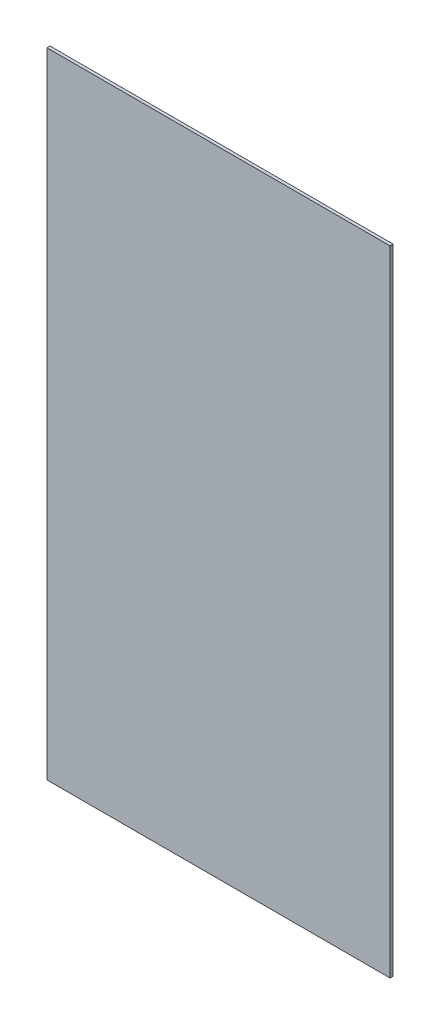
SolidWorks part; units mm, degrees
ref_plane "Front Plane" through (0, 0, 0) normal (0, 0, 1) x (1, 0, 0)
ref_plane "Top Plane" through (0, 0, 0) normal (0, 1, 0) x (1, 0, 0)
ref_plane "Right Plane" through (0, 0, 0) normal (1, 0, 0) x (0, 0, -1)
ref_plane "PZ 26.850" through (0, 0, 26.85) normal (0, 0, 1) x (1, 0, 0)
sketch "diffuser sketch" plane through (0, 0, 26.85) normal (0, 0, 1) x (1, 0, 0)
  line L0 (-164.7, -304.4) -> (164.7, -304.4)
  line L1 (164.7, -304.4) -> (164.7, 304.4)
  line L2 (164.7, 304.4) -> (-164.7, 304.4)
  line L3 (-164.7, 304.4) -> (-164.7, -304.4)
extrude "diffuser" add sketch "diffuser sketch" along normal mid plane 2.9
equation "\"diffL\" = 608.8mm"
equation "\"diffW\" = 329.4mm"
equation "\"diffT\" = 2.9mm"
equation "\"chanSlotW\" = 12.9mm"
equation "\"chanSlotDepth\" = 11.13mm"
equation "\"chanFloor\" = 1.57mm"
equation "\"chanLeg\" = 12.7mm"
equation "\"lightL\" = 604.8mm"
equation "\"lightW\" = 330.2mm"
equation "\"lightH\" = 92mm"
equation "\"lightSideFlat\" = 30mm"
equation "\"lightSlopeLen\" = 38.9mm"
equation "\"lightWingDepth\" = 50.1mm"
equation "\"lightWingFlat\" = 90.2mm"
equation "\"lightChanW\" = 99.6mm"
equation "\"lightChanStand\" = 44.1mm"
equation "\"insFlangeD\" = 12.3mm"
equation "\"insFromEnd\" = 20.7mm"
equation "\"insUpSlope\" = 20.8mm"
equation "\"gaugeH\" = 10mm"
equation "\"gaugeStepLen\" = 14mm"
equation "\"gaugeStepW0\" = 13.1mm"
equation "\"gaugeStepDW\" = 0.2mm"
equation "\"gaugeSteps\" = 5mm"
equation "\"gaugeHandleLen\" = 30mm"
equation "\"gaugeHandleW\" = 24mm"
equation "\"gaugeSlot0\" = 3mm"
equation "\"gaugeSlotD\" = 0.1mm"
equation "\"gaugeSlotDepth\" = 8mm"
equation "\"gap\" = 25.4mm"
equation "\"edgeL\" = 1mm"
equation "\"edgeW\" = 0.75mm"
equation "\"proud\" = 2.5mm"
equation "\"seatClr\" = 0.15mm"
equation "\"tongueClrZ\" = 0.1mm"
equation "\"tongueClrX\" = 0.25mm"
equation "\"tongueLen\" = 30mm"
equation "\"armSide\" = 45mm"
equation "\"armEnd\" = 20mm"
equation "\"brkW\" = 26mm"
equation "\"brkT\" = 7mm"
equation "\"brkSeatClr\" = 0.3mm"
equation "\"brkScrewSpan\" = 16mm"
equation "\"pilotD\" = 2.7mm"
equation "\"pilotDepth\" = 10mm"
equation "\"screwClrD\" = 3.9mm"
equation "\"jogBelow\" = 4mm"
equation "\"padT\" = 7mm"
equation "\"padLen\" = 36mm"
equation "\"m6Clr\" = 9mm"
equation "\"m6Slot\" = 5mm"
equation "\"flangeRelD\" = 18mm"
equation "\"flangeRelDepth\" = 1.5mm"
equation "\"relLen\" = 5mm"
equation "\"relDepth\" = 3.3mm"
equation "\"knockN\" = 100mm"
equation "\"petgcfE\" = 3000mm"
equation "\"mockExtent\" = 110mm"
equation "\"relZnear\" = 9.4mm"
equation "\"relZfar\" = 23.4mm"
equation "\"headD\" = 8mm"
equation "\"headH\" = 2.5mm"
equation "\"headFromEnd\" = 6.8mm"
equation "\"headBack\" = 16.4mm"
equation "\"sideClr\" = 0.4mm"
equation "\"cornerRelR\" = 1.5mm"
equation "\"cornerRelBack\" = 0.6mm"
equation "\"endHeadH\" = 2.8mm"
equation "\"footClr\" = 1.2mm"
equation "\"footEndClr\" = 3.5mm"
equation "\"footLift\" = 6mm"
equation "\"footBlockClr\" = 0.5mm"
equation "\"footBack\" = 50mm"
equation "\"footFwd\" = 10mm"
equation "\"footBraceEnd\" = 3mm"
equation "\"footLoadN\" = 25mm"
equation "\"spacerLen\" = 60mm"
equation "\"spacerShort\" = 0.5mm"
equation "\"spacerCham\" = 0.8mm"
equation "\"spacerPerSide\" = 3mm"
equation "\"spacerPerEnd\" = 1mm"
equation "\"toolR\" = 9mm"
equation "\"visR\" = 4mm"
equation "\"edgeR\" = 1mm"
equation "\"bendOutR\" = 5mm"
equation "\"insideR\" = 2.5mm"
equation "\"footCornerR\" = 10mm"
equation "\"footFrontR\" = 8mm"
equation "\"braceKinkR\" = 12mm"
equation "\"bedCham\" = 1mm"
equation "\"bedChamSmall\" = 0.6mm"
equation "\"soleTopR\" = 2mm"
equation "\"cornerR\" = 6mm"
equation "\"rimInR\" = 1mm"
equation "\"insFlangeH\" = 1mm"
